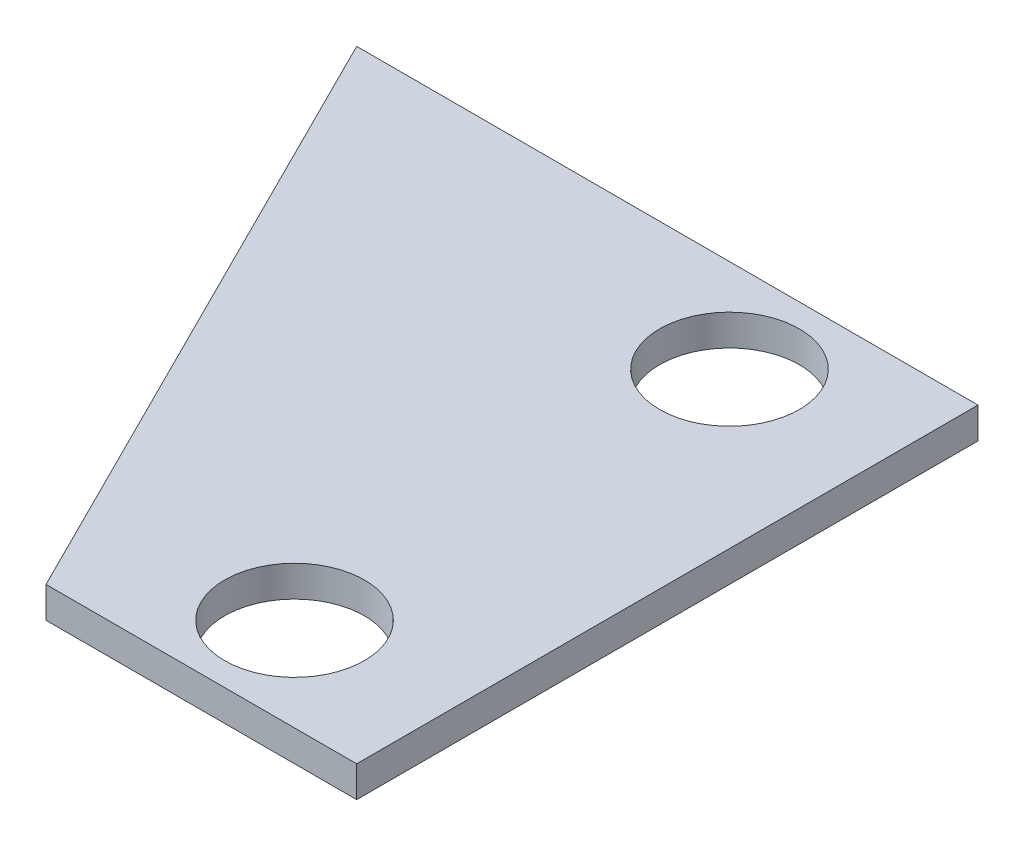
SolidWorks part; units mm, degrees
ref_plane "Ebene vorne" through (0, 0, 0) normal (0, 0, 1) x (1, 0, 0)
ref_plane "Ebene oben" through (0, 0, 0) normal (0, 1, 0) x (1, 0, 0)
ref_plane "Ebene rechts" through (0, 0, 0) normal (1, 0, 0) x (0, 0, -1)
sketch "Sketch1" plane through (0, 0, 0) normal (0, 1, 0) x (1, 0, 0)
  line L0 (0, 12.139) -> (0, -13.3155) construction
  line L1 (13.1551, 0) -> (-11.6578, 0) construction
  line L2 (-5, -10) -> (-15, 10)
  line L3 (-5, 10) -> (5, 10)
  line L4 (-5, 10) -> (-5, -10) construction
  line L5 (-5, -10) -> (5, -10)
  line L6 (5, 10) -> (5, -10)
  line L7 (-15, 10) -> (-5, 10)
  circle A0 centre (0, 7) radius 2.25
  circle A1 centre (0, -7) radius 2.25
  point P14 (0, 0)
  dimension "D4" = 4.5
  dimension "D1" = 20
  dimension "D2" = 10
  dimension "D3" = 10
  dimension "D5" = 14
extrude "Boss-Extrude1" add sketch "Sketch1" along normal blind 1
